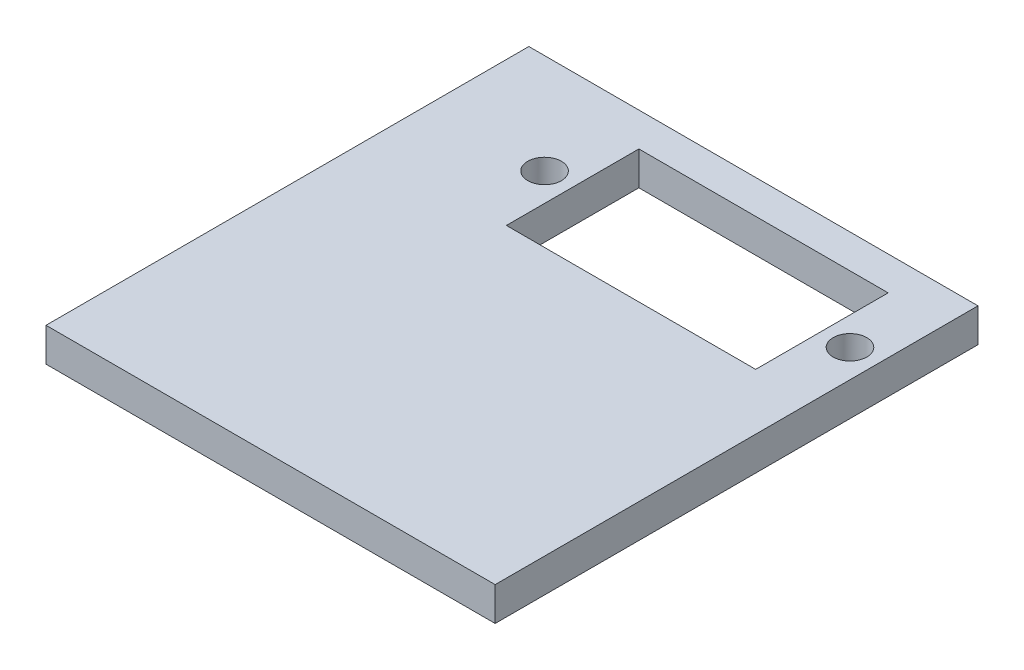
SolidWorks part; units mm, degrees
ref_plane "Front Plane" through (0, 0, 0) normal (0, 0, 1) x (1, 0, 0)
ref_plane "Top Plane" through (0, 0, 0) normal (0, 1, 0) x (1, 0, 0)
ref_plane "Right Plane" through (0, 0, 0) normal (1, 0, 0) x (0, 0, -1)
sketch "Sketch1" plane through (0, 0, 0) normal (0, 1, 0) x (1, 0, 0)
  line L1 (0, 0) -> (40, 0)
  line L2 (0, 0) -> (0, 40)
  line L3 (0, 40) -> (40, 40)
  line L4 (40, 0) -> (40, 40)
  dimension "D1" = 40
  dimension "D2" = 40
extrude "Boss-Extrude1" add sketch "Sketch1" along normal blind 3
sketch "Sketch2" plane through (0, 0, -40) normal (0, 0, -1) x (-1, 0, 0)
  line L1 (0, 3) -> (-40, 3)
  line L2 (0, 3) -> (0, 0)
  line L3 (0, 0) -> (-40, 0)
  line L4 (-40, 3) -> (-40, 0)
extrude "Boss-Extrude2" add sketch "Sketch2" along normal blind 3
sketch "Sketch3" plane through (0, 3, 0) normal (0, 1, 0) x (1, 0, 0)
  line L0 (12.8, 40) -> (35, 40)
  line L3 (40, 0) -> (40, 43) construction
  line L4 (0, 43) -> (40, 43) construction
  line L5 (12.8, 40) -> (12.8, 28.2)
  line L6 (12.8, 28.2) -> (35, 28.2)
  line L7 (35, 40) -> (35, 28.2)
  point P6 (23.9, 40)
  dimension "D1" = 5
  dimension "D2" = 11.8
  dimension "D3" = 22.2
  dimension "D4" = 3
extrude "Cut-Extrude1" cut sketch "Sketch3" against normal blind 10
sketch "Sketch4" plane through (0, 3, 0) normal (0, 1, 0) x (1, 0, 0)
  line L0 (12.8, 40) -> (12.8, 28.2) construction
  line L1 (35, 28.2) -> (35, 40) construction
  circle A0 centre (10.3, 34.1) radius 1.5
  circle A1 centre (37.5, 34.1) radius 1.5
  point P5 (12.8, 34.1)
  dimension "D1" = 3
  dimension "D2" = 2.5
  dimension "D3" = 2.5
extrude "Cut-Extrude2" cut sketch "Sketch4" against normal blind 10
